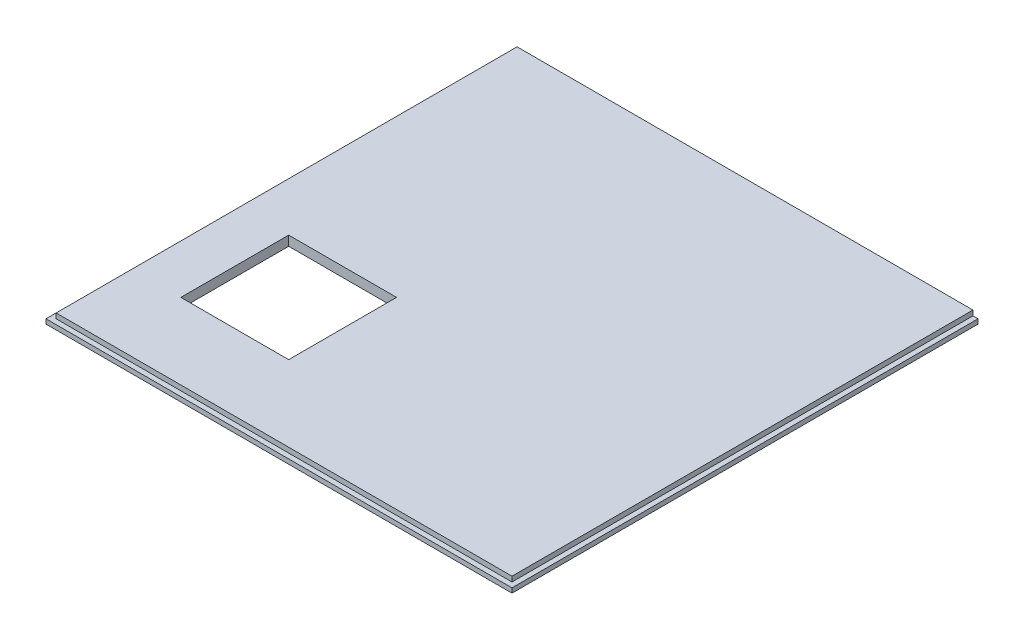
SolidWorks part; units mm, degrees
material "Plywood"
ref_plane "Front Plane" through (0, 0, 0) normal (0, 0, 1) x (1, 0, 0)
ref_plane "Top Plane" through (0, 0, 0) normal (0, 1, 0) x (1, 0, 0)
ref_plane "Right Plane" through (0, 0, 0) normal (1, 0, 0) x (0, 0, -1)
sketch "Sketch1" plane through (0, 0, 0) normal (0, 1, 0) x (1, 0, 0)
  line L0 (-235.7438, -184.9437) -> (-235.7437, -438.9437) construction
  line L1 (-438.9437, -438.9437) -> (438.9438, -438.9437)
  line L2 (-438.9437, -438.9437) -> (-438.9437, 438.9438)
  line L3 (-438.9437, 438.9438) -> (438.9438, 438.9438)
  line L4 (438.9438, -438.9437) -> (438.9438, 438.9438)
  line L5 (-438.9437, -438.9437) -> (438.9438, 438.9438) construction
  line L6 (-438.9437, 438.9438) -> (438.9438, -438.9437) construction
  line L7 (-337.3438, -83.3437) -> (-134.1438, -83.3437)
  line L8 (-337.3438, -83.3437) -> (-337.3438, -286.5437)
  line L9 (-337.3438, -286.5437) -> (-134.1438, -286.5437)
  line L10 (-134.1438, -83.3437) -> (-134.1438, -286.5437)
  line L11 (-337.3438, -83.3437) -> (-134.1438, -286.5437) construction
  line L12 (-337.3438, -286.5437) -> (-134.1438, -83.3437) construction
  line L13 (-235.7438, -184.9437) -> (-438.9437, -184.9437) construction
  point P0 (0, 0)
  point P6 (-235.7438, -184.9437)
  dimension "D1" = 877.8875
  dimension "D2" = 877.8875
  dimension "D3" = 254
  dimension "D4" = 203.2
extrude "Boss-Extrude1" add sketch "Sketch1" along normal blind 18.2562 contours L1 L4 L3 L2 L7 L10 L9 L8
sketch "Sketch3" plane through (0, 18.2562, 0) normal (0, 1, 0) x (1, 0, 0)
  line L3 (429.4188, 438.9438) -> (438.9437, 438.9437)
  line L5 (438.9437, 438.9437) -> (438.9437, -438.9437)
  line L6 (429.4188, -429.4187) -> (429.4188, 438.9438)
  line L7 (-429.4187, -429.4187) -> (429.4188, -429.4187)
  line L8 (-429.4187, 438.9438) -> (-429.4187, -429.4187)
  line L9 (429.4188, -429.4187) -> (429.4188, 438.9438)
  line L10 (-429.4187, -429.4187) -> (429.4188, -429.4187)
  line L11 (-429.4187, 438.9438) -> (-429.4187, -429.4187)
  line L12 (438.9437, -438.9437) -> (-438.9437, -438.9437)
  line L13 (-438.9437, 438.9437) -> (-438.9437, -438.9437)
  line L14 (438.9437, 438.9437) -> (-438.9437, -438.9437) construction
  line L15 (438.9437, -438.9437) -> (-438.9437, 438.9437) construction
  line L16 (-429.4187, 438.9438) -> (-438.9437, 438.9437)
  point P0 (0, 0)
  dimension "D1" = 9.525
extrude "Cut-Extrude1" cut sketch "Sketch3" against normal blind 9.525
